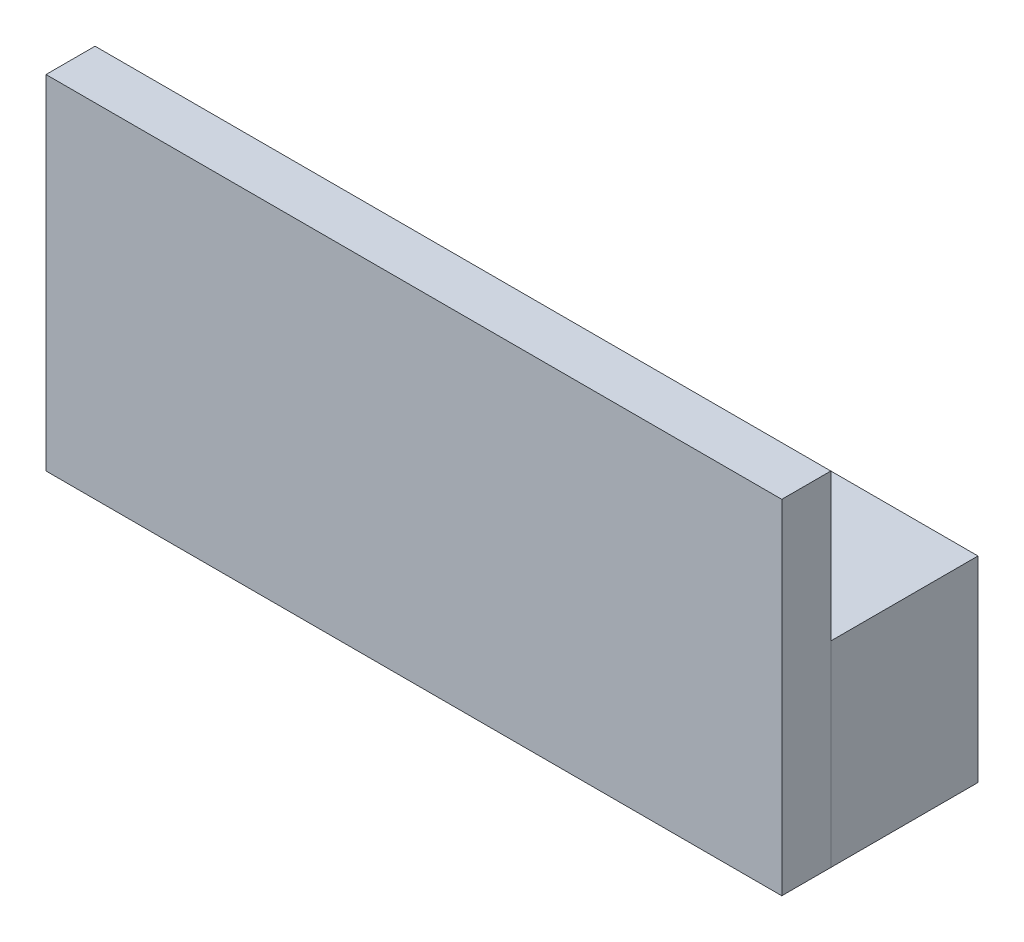
SolidWorks part; units mm, degrees
ref_plane "前视基准面" through (0, 0, 0) normal (0, 0, 1) x (1, 0, 0)
ref_plane "上视基准面" through (0, 0, 0) normal (0, 1, 0) x (1, 0, 0)
ref_plane "右视基准面" through (0, 0, 0) normal (1, 0, 0) x (0, 0, -1)
other "Configuration Table"
sketch "草图1" plane through (0, 0, 0) normal (0, 0, 1) x (1, 0, 0)
  line L1 (-10, -10) -> (10, -10)
  line L2 (-10, -10) -> (-10, 10)
  line L3 (-10, 10) -> (10, 10)
  line L4 (10, -10) -> (10, 10)
  line L5 (-10, -10) -> (10, 10) construction
  line L6 (-10, 10) -> (10, -10) construction
  point P0 (0, 0)
  dimension "D1" = 20
  dimension "D2" = 20
extrude "凸台-拉伸1" add sketch "草图1" along normal blind 10
sketch "草图2" plane through (-10, 0, 0) normal (-1, 0, 0) x (0, 0, 1)
  line L0 (5, 10) -> (5, -10) construction
  line L1 (10, 10) -> (0, 10) construction
  line L2 (10, -10) -> (0, -10) construction
  line L3 (0, 0) -> (5, 0) construction
  circle A0 centre (5, 0) radius 4
  dimension "D1" = 8
extrude "切除-拉伸1" cut sketch "草图2" against normal blind 15
sketch "草图3" plane through (0, 0, 10) normal (0, 0, 1) x (1, 0, 0)
  line L1 (10, -10) -> (-65, -10)
  line L2 (10, -10) -> (10, 25)
  line L3 (10, 25) -> (-65, 25)
  line L4 (-65, -10) -> (-65, 25)
  dimension "D1" = 75
  dimension "D2" = 35
extrude "凸台-拉伸2" add sketch "草图3" against normal blind 5 from offset 10
sketch "草图4" plane through (0, 0, 10) normal (0, 0, 1) x (1, 0, 0)
  line L4 (10, -10) -> (10, 10)
  line L5 (10, 10) -> (-10, 10)
  line L6 (-10, 10) -> (-10, -10)
  line L7 (-10, -10) -> (10, -10)
  line L8 (10, -10) -> (10, 10)
  line L9 (10, 10) -> (-10, 10)
  line L10 (-10, 10) -> (-10, -10)
  line L11 (-10, -10) -> (10, -10)
  dimension "D1" = 0
extrude "凸台-拉伸3" add sketch "草图4" along normal blind 5
